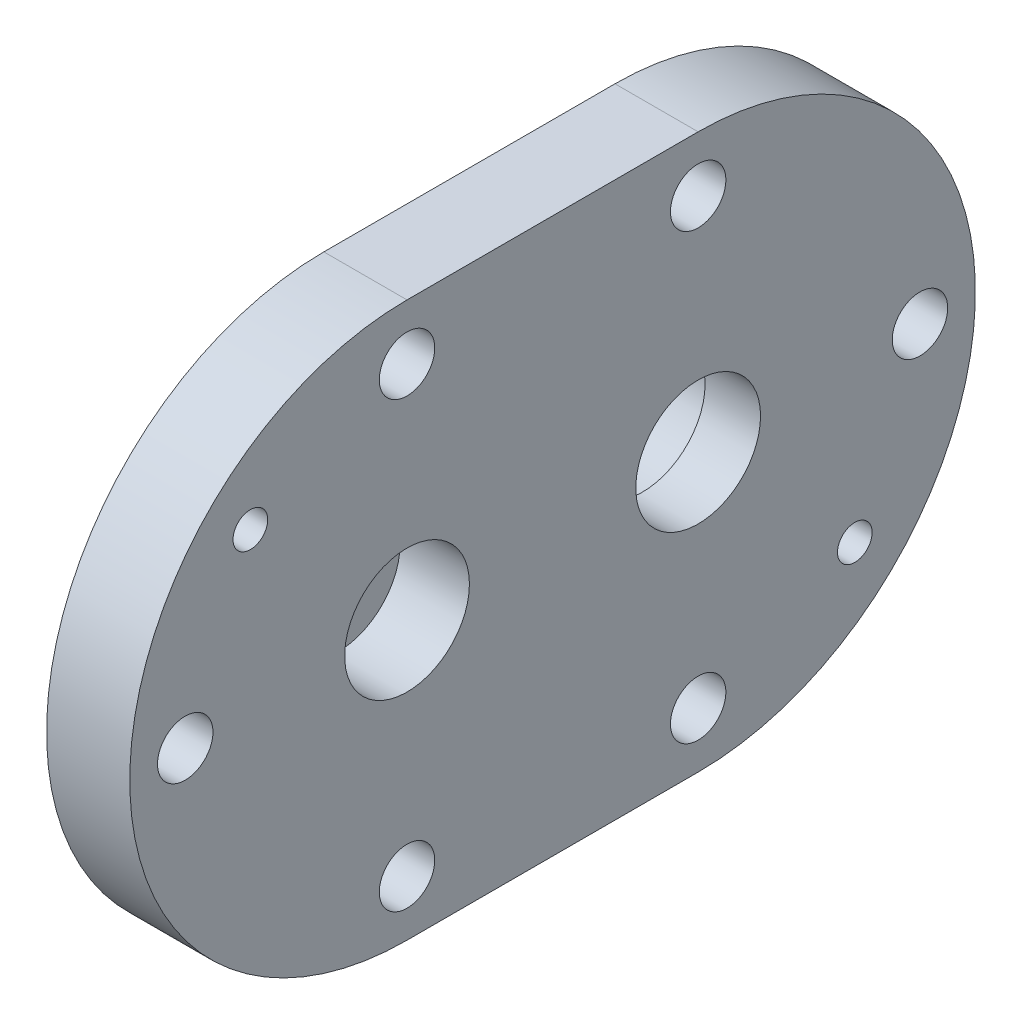
SolidWorks part; units mm, degrees
ref_plane "前视基准面" through (0, 0, 0) normal (0, 0, 1) x (1, 0, 0)
ref_plane "上视基准面" through (0, 0, 0) normal (0, 1, 0) x (1, 0, 0)
ref_plane "右视基准面" through (0, 0, 0) normal (1, 0, 0) x (0, 0, -1)
other "Configuration Table"
ref_plane "P_FLANGE" through (-42, 0, 0) normal (1, 0, 0) x (0, 0, -1)
sketch "草图1" plane through (-42, 0, 0) normal (1, 0, 0) x (0, 0, -1)
  line L0 (-104, -40) -> (-62, -40)
  line L1 (-62, 40) -> (-104, 40)
  arc A0 (-62, -40) -> (-62, 40) centre (-62, 0) ccw
  arc A1 (-104, 40) -> (-104, -40) centre (-104, 0) ccw
extrude "01_FLANGE" add sketch "草图1" along normal blind 12
ref_plane "P_02_BOSS_UP" through (-52, 0, 0) normal (1, 0, 0) x (0, 0, -1)
sketch "草图2" plane through (-52, 0, 0) normal (1, 0, 0) x (0, 0, -1)
  circle A0 centre (-104, 0) radius 16
extrude "02_BOSS_UP" add sketch "草图2" along normal blind 10
ref_plane "P_03_BOSS_LO" through (-64, 0, 0) normal (1, 0, 0) x (0, 0, -1)
sketch "草图3" plane through (-64, 0, 0) normal (1, 0, 0) x (0, 0, -1)
  circle A0 centre (-62, 0) radius 16
extrude "03_BOSS_LO" add sketch "草图3" along normal blind 22
ref_plane "P_04_BORE_UP" through (-30, 0, 0) normal (1, 0, 0) x (0, 0, -1)
sketch "草图4" plane through (-30, 0, 0) normal (1, 0, 0) x (0, 0, -1)
  circle A0 centre (-104, 0) radius 9
extrude "04_BORE_UP" cut sketch "草图4" against normal blind 10
ref_plane "P_05_BORE_LO" through (-30, 0, 0) normal (1, 0, 0) x (0, 0, -1)
sketch "草图5" plane through (-30, 0, 0) normal (1, 0, 0) x (0, 0, -1)
  circle A0 centre (-62, 0) radius 9
extrude "05_BORE_LO" cut sketch "草图5" against normal blind 10
ref_plane "P_06_RV_CAVITY" through (-64, 0, 0) normal (1, 0, 0) x (0, 0, -1)
sketch "草图6" plane through (-64, 0, 0) normal (1, 0, 0) x (0, 0, -1)
  circle A0 centre (-62, 0) radius 10
extrude "06_RV_CAVITY" cut sketch "草图6" along normal blind 26
ref_plane "P_07_RV_SEAT" through (-38, 0, 0) normal (1, 0, 0) x (0, 0, -1)
sketch "草图7" plane through (-38, 0, 0) normal (1, 0, 0) x (0, 0, -1)
  circle A0 centre (-62, 0) radius 4
ref_plane "P_08_BOLT_0" through (-43, 0, 0) normal (1, 0, 0) x (0, 0, -1)
sketch "草图8" plane through (-43, 0, 0) normal (1, 0, 0) x (0, 0, -1)
  circle A0 centre (-104, 32) radius 4
extrude "08_BOLT_0" cut sketch "草图8" along normal blind 14
ref_plane "P_08_BOLT_1" through (-43, 0, 0) normal (1, 0, 0) x (0, 0, -1)
sketch "草图9" plane through (-43, 0, 0) normal (1, 0, 0) x (0, 0, -1)
  circle A0 centre (-104, -32) radius 4
extrude "08_BOLT_1" cut sketch "草图9" along normal blind 14
ref_plane "P_08_BOLT_2" through (-43, 0, 0) normal (1, 0, 0) x (0, 0, -1)
sketch "草图10" plane through (-43, 0, 0) normal (1, 0, 0) x (0, 0, -1)
  circle A0 centre (-62, 32) radius 4
extrude "08_BOLT_2" cut sketch "草图10" along normal blind 14
ref_plane "P_08_BOLT_3" through (-43, 0, 0) normal (1, 0, 0) x (0, 0, -1)
sketch "草图11" plane through (-43, 0, 0) normal (1, 0, 0) x (0, 0, -1)
  circle A0 centre (-62, -32) radius 4
extrude "08_BOLT_3" cut sketch "草图11" along normal blind 14
ref_plane "P_08_BOLT_4" through (-43, 0, 0) normal (1, 0, 0) x (0, 0, -1)
sketch "草图12" plane through (-43, 0, 0) normal (1, 0, 0) x (0, 0, -1)
  circle A0 centre (-136, 0) radius 4
extrude "08_BOLT_4" cut sketch "草图12" along normal blind 14
ref_plane "P_08_BOLT_5" through (-43, 0, 0) normal (1, 0, 0) x (0, 0, -1)
sketch "草图13" plane through (-43, 0, 0) normal (1, 0, 0) x (0, 0, -1)
  circle A0 centre (-30, 0) radius 4
extrude "08_BOLT_5" cut sketch "草图13" along normal blind 14
ref_plane "P_09_DOWEL_0" through (-43, 0, 0) normal (1, 0, 0) x (0, 0, -1)
sketch "草图14" plane through (-43, 0, 0) normal (1, 0, 0) x (0, 0, -1)
  circle A0 centre (-126.6, 22.6) radius 2.5
extrude "09_DOWEL_0" cut sketch "草图14" along normal blind 14
ref_plane "P_09_DOWEL_1" through (-43, 0, 0) normal (1, 0, 0) x (0, 0, -1)
sketch "草图15" plane through (-43, 0, 0) normal (1, 0, 0) x (0, 0, -1)
  circle A0 centre (-39.4, -22.6) radius 2.5
extrude "09_DOWEL_1" cut sketch "草图15" along normal blind 14
